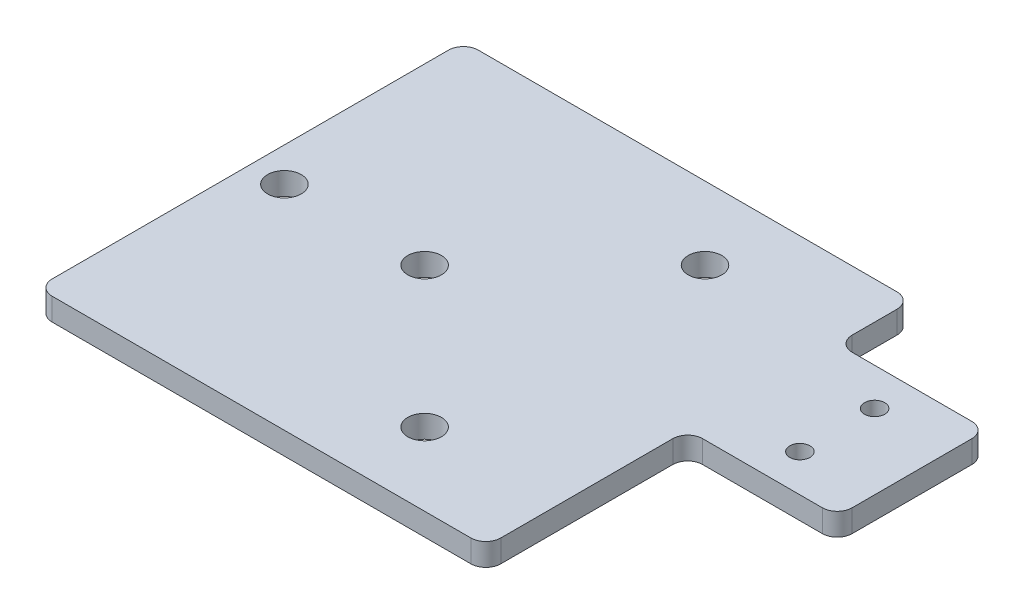
SolidWorks part; units mm, degrees
ref_plane "Front Plane" through (0, 0, 0) normal (0, 0, 1) x (1, 0, 0)
ref_plane "Top Plane" through (0, 0, 0) normal (0, 1, 0) x (1, 0, 0)
ref_plane "Right Plane" through (0, 0, 0) normal (1, 0, 0) x (0, 0, -1)
sketch "Sketch1" plane through (0, 0, 0) normal (0, 1, 0) x (1, 0, 0)
  line L1 (-30, 28.5) -> (30, 28.5)
  line L2 (-30, 28.5) -> (-30, -28.5)
  line L3 (-30, -28.5) -> (30, -28.5)
  line L4 (30, 28.5) -> (30, -28.5)
  line L5 (-30, 28.5) -> (30, -28.5) construction
  line L6 (-30, -28.5) -> (30, 28.5) construction
  point P0 (0, 0)
  point P6 (-25.437, 0)
  point P7 (-6.687, 0)
  point P8 (12.063, 18.75)
  point P9 (12.063, -18.75)
  point P10 (0, 0)
  point P13 (6.1579, 16.6579)
  dimension "D1" = 60
  dimension "D2" = 57
  dimension "D3" = 4.563
  dimension "D4" = 18.75
  dimension "D5" = 18.75
  dimension "D6" = 18.75
  dimension "D7" = 18.75
extrude "Boss-Extrude1" add sketch "Sketch1" along normal blind 3
sketch "Sketch2" plane through (0, 3, 0) normal (0, 1, 0) x (1, 0, 0)
  point P0 (-25.437, 0)
  point P1 (-6.687, 0)
  point P3 (12.063, 18.75)
  point P5 (12.063, -18.75)
hole_wizard "Ø4.5 (4.5) Diameter Hole1" positions "Sketch2" profile "Sketch3" hole size "Ø4.5" standard "ANSI Metric"
sketch "Sketch3" plane through (-25.437, 3, 0) normal (1, 0, 0) x (0, 0, 1)
  line L0 (0, 0) -> (0, 16.3519)
  line L1 (0, 16.3519) -> (2.25, 15)
  line L2 (2.25, 15) -> (2.25, 0)
  line L5 (2.25, 0) -> (0, 0)
  line L10 (0, 16.3519) -> (-2.25, 15) construction
  line L11 (0, -6.35) -> (0, 107.95) construction
  dimension "Hole Dia." = 4.5
  dimension "Hole Depth" = 15
  dimension "Drill Angle" = 118
sketch "Sketch4" plane through (0, 3, 0) normal (0, 1, 0) x (1, 0, 0)
  line L0 (30, -28.5) -> (30, 28.5) construction
  line L1 (50, -1.5) -> (30, -1.5)
  line L2 (50, -1.5) -> (50, 18.5)
  line L3 (50, 18.5) -> (30, 18.5)
  line L4 (30, -1.5) -> (30, 18.5)
  line L5 (50, -1.5) -> (30, 18.5) construction
  line L6 (50, 18.5) -> (30, -1.5) construction
  line L7 (30, 28.5) -> (-30, 28.5) construction
  point P0 (40, 8.5)
  point P7 (40, 9.9959)
  dimension "D1" = 20
  dimension "D2" = 20
  dimension "D3" = 10
extrude "Boss-Extrude2" add sketch "Sketch4" against normal blind 3
sketch "Sketch5" plane through (0, 3, 0) normal (0, 1, 0) x (1, 0, 0)
  line L0 (40, 13.5) -> (40, 3.5) construction
  point P3 (40, 8.5)
  point P4 (40, 3.5)
  point P6 (40, 13.5)
  dimension "D1" = 10
hole_wizard "Ø2.7 (2.7) Diameter Hole1" positions "Sketch5" profile "Sketch6" hole size "Ø2.7" standard "ANSI Metric"
sketch "Sketch6" plane through (40, 3, -13.5) normal (1, 0, 0) x (0, 0, 1)
  line L0 (0, 0) -> (0, 15.8112)
  line L1 (0, 15.8112) -> (1.35, 15)
  line L2 (1.35, 15) -> (1.35, 0)
  line L5 (1.35, 0) -> (0, 0)
  line L10 (0, 15.8112) -> (-1.35, 15) construction
  line L11 (0, -6.35) -> (0, 107.95) construction
  dimension "Hole Dia." = 2.7
  dimension "Hole Depth" = 15
  dimension "Drill Angle" = 118
fillet "Fillet1" radius 2 8 edges at (-30, 1.5, 28.5) (-30, 1.5, -28.5) (30, 1.5, -28.5) (30, 1.5, -18.5) (50, 1.5, -18.5) (50, 1.5, 1.5) (30, 1.5, 1.5) (30, 1.5, 28.5)
